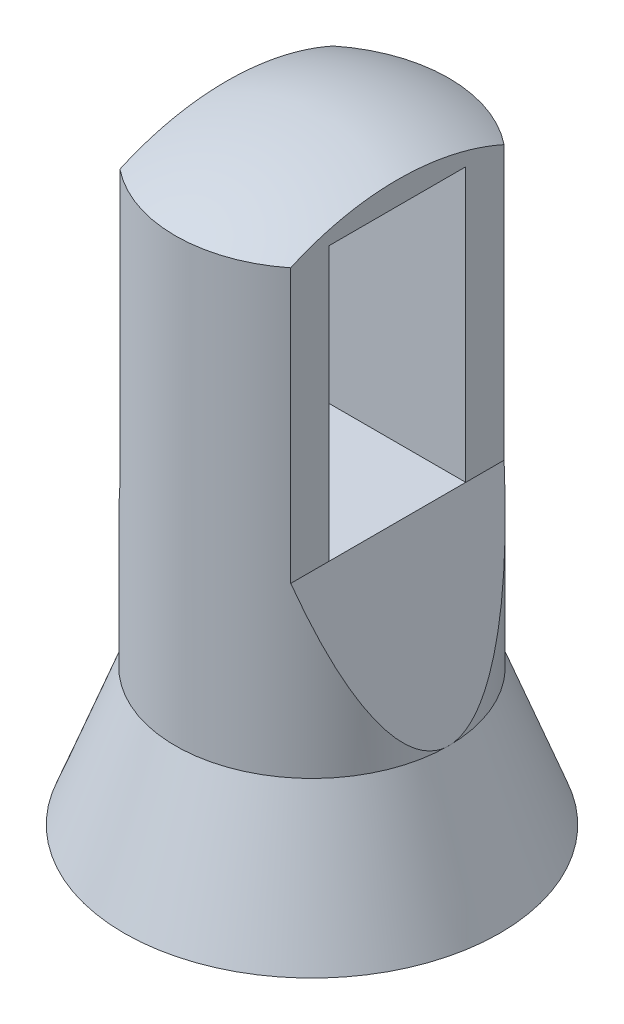
SolidWorks part; units mm, degrees
ref_plane "Front Plane" through (0, 0, 0) normal (0, 0, 1) x (1, 0, 0)
ref_plane "Top Plane" through (0, 0, 0) normal (0, 1, 0) x (1, 0, 0)
ref_plane "Right Plane" through (0, 0, 0) normal (1, 0, 0) x (0, 0, -1)
sketch "Sketch1" plane through (0, 0, 0) normal (0, 0, 1) x (1, 0, 0)
  line L0 (0, 0) -> (0, 120.4696) construction
  line L1 (0, 0) -> (34.925, 0)
  line L2 (34.925, 0) -> (25.4, 25.4)
  line L3 (25.4, 25.4) -> (25.4, 107.4941)
  line L5 (0, 114.3) -> (0, 0)
  line L6 (0, 120.4696) -> (106.8301, 120.4696) construction
  arc A0 (25.4, 107.4941) -> (0, 114.3) centre (0, 63.5) ccw
  point P12 (25.4, 25.4)
  dimension "D5" = 50.8
  dimension "D1" = 34.925
  dimension "D2" = 25.4
  dimension "D3" = 25.4
  dimension "D4" = 114.3
revolve "Revolve1" add sketch "Sketch1" angle 360 about L5
sketch "Sketch2" plane through (0, 0, 0) normal (0, 0, 1) x (1, 0, 0)
  line L0 (0, 0) -> (0, 119.3006) construction
  line L1 (-15.875, 118.2278) -> (-15.875, -6.6096)
  line L2 (15.875, 118.2278) -> (15.875, -6.6096)
  line L3 (25.4, 107.4941) -> (-25.4, 107.4941) construction
  line L4 (15.875, 107.4941) -> (-15.875, 107.4941)
  line L5 (15.875, 107.4941) -> (15.875, 56.6941)
  line L6 (15.875, 56.6941) -> (-15.875, 56.6941)
  line L7 (-15.875, 107.4941) -> (-15.875, 56.6941)
  line L8 (-15.875, 56.6941) -> (-15.875, 120.0713)
  line L9 (-25.4, 25.4) -> (-25.4, 114.0299) construction
  line L10 (-25.4, 25.4) -> (-15.875, 56.6941)
  line L11 (-34.925, 0) -> (-25.4, 25.4) construction
  line L12 (-25.4, 25.4) -> (-25.4, 110.5034)
  line L13 (-15.875, 56.6941) -> (-15.875, 113.0803)
  line L14 (-15.875, 113.0803) -> (-25.4, 113.0803) construction
  line L15 (-25.4, 113.0803) -> (-25.4, 25.4)
  line L16 (25.4, 25.4) -> (-25.4, 25.4) construction
  point P13 (-34.925, 0)
  point P14 (-32.0377, 0)
  point P16 (-25.4, 25.4)
  point P18 (0, 0)
  point P28 (0, 0)
  point P29 (0, 0)
  point P30 (0, 0)
  point P31 (0, 0)
  point P32 (0, 0)
  point P33 (0, 0)
  dimension "D1" = 15.875
  dimension "D2" = 50.8
  dimension "D3" = 87.6803
ref_plane "Plane1" through (0, 0, 0) normal (0, 0, 1) x (1, 0, 0)
sketch "Sketch6" plane through (0, 0, 0) normal (0, 0, 1) x (1, 0, 0)
  line L0 (-15.875, 56.6941) -> (-25.4, 25.4)
  line L1 (-15.875, 56.6941) -> (-15.875, 127.8957)
  line L2 (-15.875, 127.8957) -> (-29.7787, 127.8957)
  line L3 (-25.4, 25.4) -> (-28.7087, 28.7087)
  line L4 (-28.7087, 28.7087) -> (-29.7787, 127.8957)
  line L5 (0, 0) -> (0, 144.903) construction
  line L6 (15.875, 127.8957) -> (29.7787, 127.8957)
  line L7 (28.7087, 28.7087) -> (29.7787, 127.8957)
  line L8 (25.4, 25.4) -> (28.7087, 28.7087)
  line L9 (15.875, 56.6941) -> (25.4, 25.4)
  line L10 (15.875, 56.6941) -> (15.875, 127.8957)
extrude "Cut-Extrude2" cut sketch "Sketch6" against normal through all both and the other way through all from surface at 0 starting at plane "Plane1"
sketch "Sketch7" plane through (15.875, 0, 0) normal (1, 0, 0) x (0, 0, -1)
  line L0 (19.8279, 56.6941) -> (-19.8279, 56.6941) construction
  line L1 (-12.7, 56.6941) -> (12.7, 56.6941)
  line L2 (-12.7, 56.6941) -> (-12.7, 107.4941)
  line L3 (-12.7, 107.4941) -> (12.7, 107.4941)
  line L4 (12.7, 56.6941) -> (12.7, 107.4941)
  line L6 (0, 56.6941) -> (0, 120.0713) construction
  point P8 (0, 107.4941)
  dimension "D1" = 25.4
  dimension "D2" = 50.8
extrude "Cut-Extrude3" cut sketch "Sketch7" against normal blind 254
